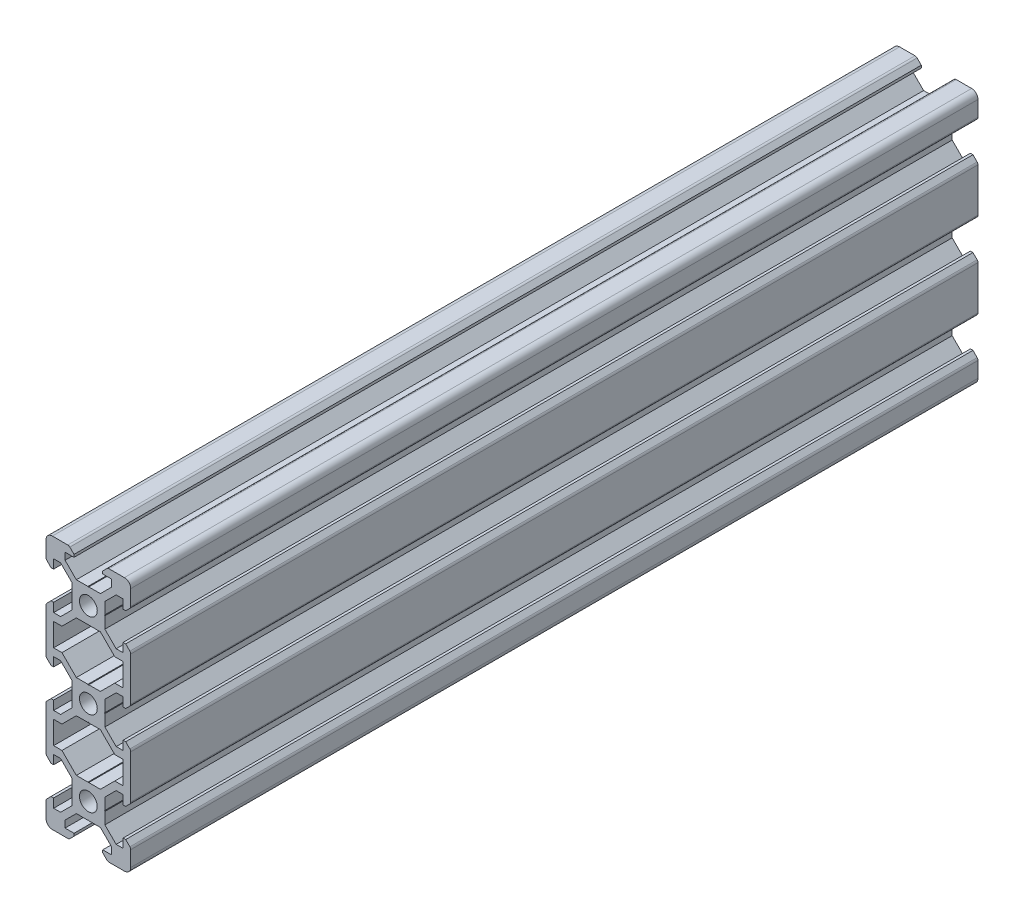
SolidWorks part; units mm, degrees
material "6063-T5"
ref_plane "Front" through (0, 0, 0) normal (0, 0, 1) x (1, 0, 0)
ref_plane "Top" through (0, 0, 0) normal (0, 1, 0) x (1, 0, 0)
ref_plane "Right" through (0, 0, 0) normal (1, 0, 0) x (0, 0, -1)
sketch "Sketch1" plane through (0, 0, 0) normal (0, 0, 1) x (1, 0, 0)
  line L0 (-8.5, 10) -> (-10, 8.5) construction
  line L1 (-8.5, 10) -> (-4.8628, 10)
  line L2 (-10, 8.5) -> (-10, 4.8628)
  line L3 (25.9287, -20) -> (-28.3599, -20) construction
  line L4 (10, 8.5) -> (10, 4.8628)
  line L5 (-10, 10) -> (10, -10) construction
  line L6 (-10, -10) -> (10, 10) construction
  line L7 (8.2, -5.5) -> (8.2, -3.3865)
  line L8 (-8.2, -5.5) -> (-8.2, -3.3865)
  line L9 (-5.5, 8.2) -> (-3.3865, 8.2)
  line L10 (-8.2, -12.7) -> (-8.2, -7.3)
  line L11 (-3.9005, 2.8395) -> (-6.561, 5.5)
  line L12 (-6.561, 5.5) -> (-8.2, 5.5)
  line L13 (-2.8395, -3.9005) -> (-0.1, -3.9005)
  line L14 (-3.9005, -2.8395) -> (-3.9005, -0.1)
  line L15 (-2.8395, 3.9005) -> (-0.1, 3.9005)
  line L16 (3.9005, -2.8395) -> (3.9005, -0.1)
  line L17 (-8.2, 3.3865) -> (-8.81, 3.3865)
  line L18 (-8.81, 3.3865) -> (-9.7976, 4.3741)
  line L19 (8.5, 10) -> (10, 8.5) construction
  line L20 (-2.8395, 3.9005) -> (-5.5, 6.561)
  line L21 (-5.5, 6.561) -> (-5.5, 8.2)
  line L22 (-3.3865, 8.2) -> (-3.3865, 8.81)
  line L23 (-3.3865, 8.81) -> (-4.3741, 9.7976)
  line L24 (0, 24.069) -> (0, -33.8154) construction
  line L25 (3.3865, 8.81) -> (4.3741, 9.7976)
  line L26 (3.3865, 8.2) -> (3.3865, 8.81)
  line L27 (5.5, 6.561) -> (5.5, 8.2)
  line L28 (2.8395, 3.9005) -> (5.5, 6.561)
  line L29 (3.3865, 8.2) -> (5.5, 8.2)
  line L30 (4.8628, 10) -> (8.5, 10)
  line L31 (-0.1, 3.9005) -> (0, 3.8005)
  line L32 (0.1, 3.9005) -> (0, 3.8005)
  line L33 (0.1, 3.9005) -> (2.8395, 3.9005)
  line L34 (25.9287, 0) -> (-28.3459, 0) construction
  line L35 (-0.1, -3.9005) -> (0, -3.8005)
  line L36 (0.1, -3.9005) -> (0, -3.8005)
  line L37 (0.1, -3.9005) -> (2.8395, -3.9005)
  line L38 (-3.9005, 0.1) -> (-3.8005, 0)
  line L39 (-3.8005, 0) -> (-3.9005, -0.1)
  line L40 (-3.9005, 0.1) -> (-3.9005, 2.8395)
  line L41 (3.9005, 0.1) -> (3.8005, 0)
  line L42 (3.8005, 0) -> (3.9005, -0.1)
  line L43 (3.9005, 0.1) -> (3.9005, 2.8395)
  line L44 (8.81, 3.3865) -> (9.7976, 4.3741)
  line L45 (8.2, 3.3865) -> (8.81, 3.3865)
  line L46 (6.561, 5.5) -> (8.2, 5.5)
  line L47 (3.9005, 2.8395) -> (6.561, 5.5)
  line L48 (2.8395, -3.9005) -> (5.5, -6.561)
  line L49 (3.9005, -2.8395) -> (6.561, -5.5)
  line L50 (-2.8395, -3.9005) -> (-5.5, -6.561)
  line L51 (-3.9005, -2.8395) -> (-6.561, -5.5)
  line L52 (6.561, -5.5) -> (8.2, -5.5)
  line L53 (-6.561, -5.5) -> (-8.2, -5.5)
  line L54 (-8.81, -3.3865) -> (-9.7976, -4.3741)
  line L55 (-8.2, -3.3865) -> (-8.81, -3.3865)
  line L56 (8.81, -3.3865) -> (9.7976, -4.3741)
  line L57 (8.2, -3.3865) -> (8.81, -3.3865)
  line L58 (8.2, 3.3865) -> (8.2, 5.5)
  line L59 (10, -4.8628) -> (10, -15.1372)
  line L60 (-8.2, 3.3865) -> (-8.2, 5.5)
  line L61 (-10, -4.8628) -> (-10, -15.1372)
  line L62 (-28.3459, -10) -> (-10, -10) construction
  line L63 (-3.9005, -20.1) -> (-3.9005, -22.8395)
  line L64 (-3.9005, -20.1) -> (-3.8005, -20)
  line L65 (-3.8005, -20) -> (-3.9005, -19.9)
  line L66 (3.9005, -20.1) -> (3.9005, -22.8395)
  line L67 (3.9005, -20.1) -> (3.8005, -20)
  line L68 (3.8005, -20) -> (3.9005, -19.9)
  line L69 (6.561, -14.5) -> (8.2, -14.5)
  line L70 (3.9005, -17.1605) -> (6.561, -14.5)
  line L71 (3.9005, -17.1605) -> (3.9005, -19.9)
  line L72 (-3.9005, -17.1605) -> (-3.9005, -19.9)
  line L73 (-3.9005, -17.1605) -> (-6.561, -14.5)
  line L74 (-6.561, -14.5) -> (-8.2, -14.5)
  line L75 (-8.2, -16.6135) -> (-8.81, -16.6135)
  line L76 (-8.81, -16.6135) -> (-9.7976, -15.6259)
  line L77 (8.2, -16.6135) -> (8.81, -16.6135)
  line L78 (8.81, -16.6135) -> (9.7976, -15.6259)
  line L79 (-2.8395, -16.0995) -> (-5.5, -13.439)
  line L80 (-2.8395, -16.0995) -> (-0.1, -16.0995)
  line L81 (-0.1, -16.0995) -> (0, -16.1995)
  line L82 (0.1, -16.0995) -> (0, -16.1995)
  line L83 (0.1, -16.0995) -> (2.8395, -16.0995)
  line L84 (2.8395, -16.0995) -> (5.5, -13.439)
  line L85 (-8.2, -16.6135) -> (-8.2, -14.5)
  line L86 (8.2, -16.6135) -> (8.2, -14.5)
  line L87 (2.8395, -23.9005) -> (5.5, -26.561)
  line L88 (-2.8395, -23.9005) -> (-5.5, -26.561)
  line L89 (-0.1, -23.9005) -> (0, -23.8005)
  line L90 (0.1, -23.9005) -> (0, -23.8005)
  line L91 (0.1, -23.9005) -> (2.8395, -23.9005)
  line L92 (-2.8395, -23.9005) -> (-0.1, -23.9005)
  line L93 (-8.2, -23.3865) -> (-8.2, -25.5)
  line L94 (-8.2, -23.3865) -> (-8.81, -23.3865)
  line L95 (-8.81, -23.3865) -> (-9.7976, -24.3741)
  line L96 (8.2, -23.3865) -> (8.2, -25.5)
  line L97 (8.2, -23.3865) -> (8.81, -23.3865)
  line L98 (8.81, -23.3865) -> (9.7976, -24.3741)
  line L99 (8.2, -27.3) -> (8.2, -32.7)
  line L100 (10, -35.1372) -> (10, -24.8628)
  line L101 (-10, -35.1372) -> (-10, -24.8628)
  line L102 (-8.2, -27.3) -> (-8.2, -32.7)
  line L103 (3.9005, -22.8395) -> (6.561, -25.5)
  line L104 (-3.9005, -22.8395) -> (-6.561, -25.5)
  line L105 (6.239, -27.3) -> (8.2, -27.3)
  line L106 (-6.239, -27.3) -> (-8.2, -27.3)
  line L107 (-6.561, -25.5) -> (-8.2, -25.5)
  line L108 (6.561, -25.5) -> (8.2, -25.5)
  line L109 (5.5, -26.561) -> (6.239, -27.3)
  line L110 (-5.5, -26.561) -> (-6.239, -27.3)
  line L111 (8.2, -34.5) -> (8.2, -36.6135)
  line L112 (8.2, -36.6135) -> (8.81, -36.6135)
  line L113 (8.81, -36.6135) -> (9.7976, -35.6259)
  line L114 (-8.2, -34.5) -> (-8.2, -36.6135)
  line L115 (-6.239, -7.3) -> (-8.2, -7.3)
  line L116 (-5.5, -6.561) -> (-6.239, -7.3)
  line L117 (6.239, -7.3) -> (8.2, -7.3)
  line L118 (5.5, -6.561) -> (6.239, -7.3)
  line L119 (-6.239, -12.7) -> (-8.2, -12.7)
  line L120 (-5.5, -13.439) -> (-6.239, -12.7)
  line L121 (5.5, -13.439) -> (6.239, -12.7)
  line L122 (6.239, -12.7) -> (8.2, -12.7)
  line L123 (8.2, -12.7) -> (8.2, -7.3)
  line L124 (-8.2, -36.6135) -> (-8.81, -36.6135)
  line L125 (10, -10) -> (25.9287, -10) construction
  line L126 (-8.81, -36.6135) -> (-9.7976, -35.6259)
  line L128 (-0.1, -36.0995) -> (0, -36.1995)
  line L129 (0.1, -36.0995) -> (0, -36.1995)
  line L130 (0.1, -36.0995) -> (2.8395, -36.0995)
  line L131 (-6.561, -34.5) -> (-8.2, -34.5)
  line L132 (6.561, -34.5) -> (8.2, -34.5)
  line L133 (6.239, -32.7) -> (8.2, -32.7)
  line L134 (-6.239, -32.7) -> (-8.2, -32.7)
  line L135 (-5.5, -33.439) -> (-6.239, -32.7)
  line L136 (5.5, -33.439) -> (6.239, -32.7)
  line L137 (-8.81, -43.3865) -> (-9.7976, -44.3741)
  line L138 (-8.2, -43.3865) -> (-8.81, -43.3865)
  line L139 (-8.2, -43.3865) -> (-8.2, -45.5)
  line L140 (-6.561, -45.5) -> (-8.2, -45.5)
  line L141 (-10, -48.5) -> (-10, -44.8628)
  line L142 (-8.5, -50) -> (-4.8628, -50)
  line L143 (-3.3865, -48.81) -> (-4.3741, -49.7976)
  line L144 (-3.3865, -48.2) -> (-3.3865, -48.81)
  line L145 (-5.5, -48.2) -> (-3.3865, -48.2)
  line L146 (-5.5, -46.561) -> (-5.5, -48.2)
  line L147 (3.3865, -48.2) -> (5.5, -48.2)
  line L148 (3.3865, -48.2) -> (3.3865, -48.81)
  line L149 (3.3865, -48.81) -> (4.3741, -49.7976)
  line L150 (4.8628, -50) -> (8.5, -50)
  line L151 (5.5, -46.561) -> (5.5, -48.2)
  line L152 (6.561, -45.5) -> (8.2, -45.5)
  line L153 (8.2, -43.3865) -> (8.2, -45.5)
  line L154 (10, -48.5) -> (10, -44.8628)
  line L155 (8.81, -43.3865) -> (9.7976, -44.3741)
  line L156 (8.2, -43.3865) -> (8.81, -43.3865)
  line L157 (-0.1, -43.9005) -> (0, -43.8005)
  line L158 (0.1, -43.9005) -> (0, -43.8005)
  line L159 (-2.8395, -43.9005) -> (-0.1, -43.9005)
  line L160 (0.1, -43.9005) -> (2.8395, -43.9005)
  line L161 (3.9005, -40.1) -> (3.8005, -40)
  line L162 (3.8005, -40) -> (3.9005, -39.9)
  line L163 (3.9005, -37.1605) -> (3.9005, -39.9)
  line L164 (3.9005, -40.1) -> (3.9005, -42.8395)
  line L165 (-2.8395, -36.0995) -> (-0.1, -36.0995)
  line L166 (-2.8395, -43.9005) -> (-5.5, -46.561)
  line L167 (-3.9005, -37.1605) -> (-3.9005, -39.9)
  line L168 (-3.8005, -40) -> (-3.9005, -39.9)
  line L169 (-3.9005, -40.1) -> (-3.8005, -40)
  line L170 (-3.9005, -42.8395) -> (-6.561, -45.5)
  line L171 (2.8395, -43.9005) -> (5.5, -46.561)
  line L172 (3.9005, -42.8395) -> (6.561, -45.5)
  line L173 (3.9005, -37.1605) -> (6.561, -34.5)
  line L174 (2.8395, -36.0995) -> (5.5, -33.439)
  line L175 (-3.9005, -42.8395) -> (-3.9005, -40.1)
  line L176 (-6.561, -34.5) -> (-3.9005, -37.1605)
  line L177 (-5.5, -33.439) -> (-2.8395, -36.0995)
  circle A0 centre (0, 0) radius 2.1
  arc A1 (-8.5, 10) -> (-10, 8.5) centre (-8.5, 8.5) ccw
  arc A2 (10, 8.5) -> (8.5, 10) centre (8.5, 8.5) ccw
  arc A3 (-4.3741, 9.7976) -> (-4.8628, 10) centre (-4.8628, 9.3088) ccw
  arc A4 (4.8628, 10) -> (4.3741, 9.7976) centre (4.8628, 9.3088) ccw
  circle A5 centre (0, -20) radius 2.1
  arc A6 (9.7976, 4.3741) -> (10, 4.8628) centre (9.3088, 4.8628) ccw
  arc A7 (-10, 4.8628) -> (-9.7976, 4.3741) centre (-9.3088, 4.8628) ccw
  arc A8 (-10, -4.8628) -> (-9.7976, -4.3741) centre (-9.3088, -4.8628) cw
  arc A9 (9.7976, -4.3741) -> (10, -4.8628) centre (9.3088, -4.8628) cw
  arc A10 (-10, -15.1372) -> (-9.7976, -15.6259) centre (-9.3088, -15.1372) ccw
  arc A11 (9.7976, -15.6259) -> (10, -15.1372) centre (9.3088, -15.1372) ccw
  arc A12 (-10, -24.8628) -> (-9.7976, -24.3741) centre (-9.3088, -24.8628) cw
  arc A13 (9.7976, -24.3741) -> (10, -24.8628) centre (9.3088, -24.8628) cw
  arc A14 (9.7976, -35.6259) -> (10, -35.1372) centre (9.3088, -35.1372) ccw
  arc A15 (-10, -35.1372) -> (-9.7976, -35.6259) centre (-9.3088, -35.1372) ccw
  circle A16 centre (0, -40) radius 2.1
  arc A17 (-10, -44.8628) -> (-9.7976, -44.3741) centre (-9.3088, -44.8628) cw
  arc A18 (-8.5, -50) -> (-10, -48.5) centre (-8.5, -48.5) cw
  arc A19 (-4.3741, -49.7976) -> (-4.8628, -50) centre (-4.8628, -49.3088) cw
  arc A20 (4.8628, -50) -> (4.3741, -49.7976) centre (4.8628, -49.3088) cw
  arc A21 (10, -48.5) -> (8.5, -50) centre (8.5, -48.5) cw
  arc A22 (9.7976, -44.3741) -> (10, -44.8628) centre (9.3088, -44.8628) cw
  point P17 (-9.25, 9.25)
  point P21 (9.25, 9.25)
  dimension "D2" = 4.2
  dimension "D4" = 1.5
  dimension "D3" = 20
  dimension "D5" = 0.529
  dimension "D6" = 6.773
  dimension "D7" = 90
  dimension "D8" = 11
  dimension "D9" = 0.61
  dimension "D10" = 0.1
  dimension "D11" = 0.1
  dimension "D12" = 0.1
  dimension "D13" = 0.1
  dimension "D14" = 5.679
  dimension "D15" = 1.639
  dimension "D16" = 1.8
  dimension "D17" = 90
  dimension "D18" = 6.773
  dimension "D19" = 90
  dimension "D20" = 20
  dimension "D21" = 1.8
extrude "Boss-Extrude2" add sketch "Sketch1" along normal blind 200
